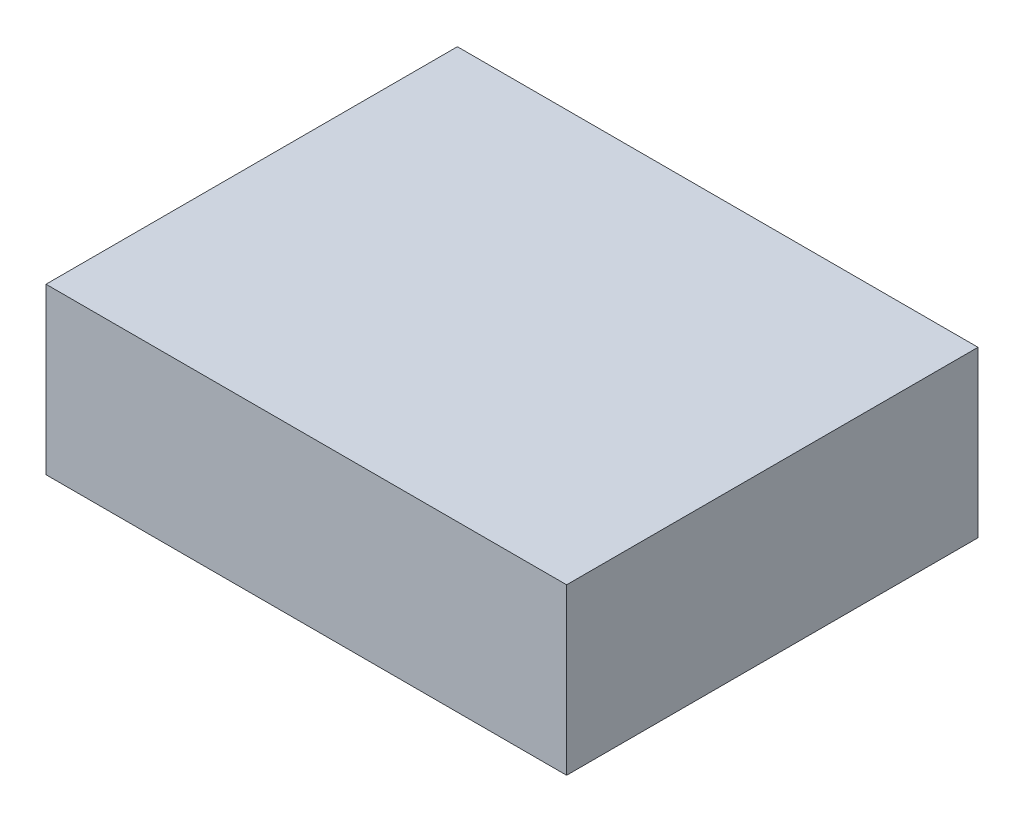
SolidWorks part; units mm, degrees
ref_plane "Front Plane" through (0, 0, 0) normal (0, 0, 1) x (1, 0, 0)
ref_plane "Top Plane" through (0, 0, 0) normal (0, 1, 0) x (1, 0, 0)
ref_plane "Right Plane" through (0, 0, 0) normal (1, 0, 0) x (0, 0, -1)
sketch "Sketch1" plane through (0, 0, 0) normal (0, 1, 0) x (1, 0, 0)
  line L1 (-20.3017, 5.5483) -> (11.2539, 5.5483)
  line L2 (-20.3017, 5.5483) -> (-20.3017, -19.3864)
  line L3 (-20.3017, -19.3864) -> (11.2539, -19.3864)
  line L4 (11.2539, 5.5483) -> (11.2539, -19.3864)
extrude "Boss-Extrude1" add sketch "Sketch1" along normal blind 10
